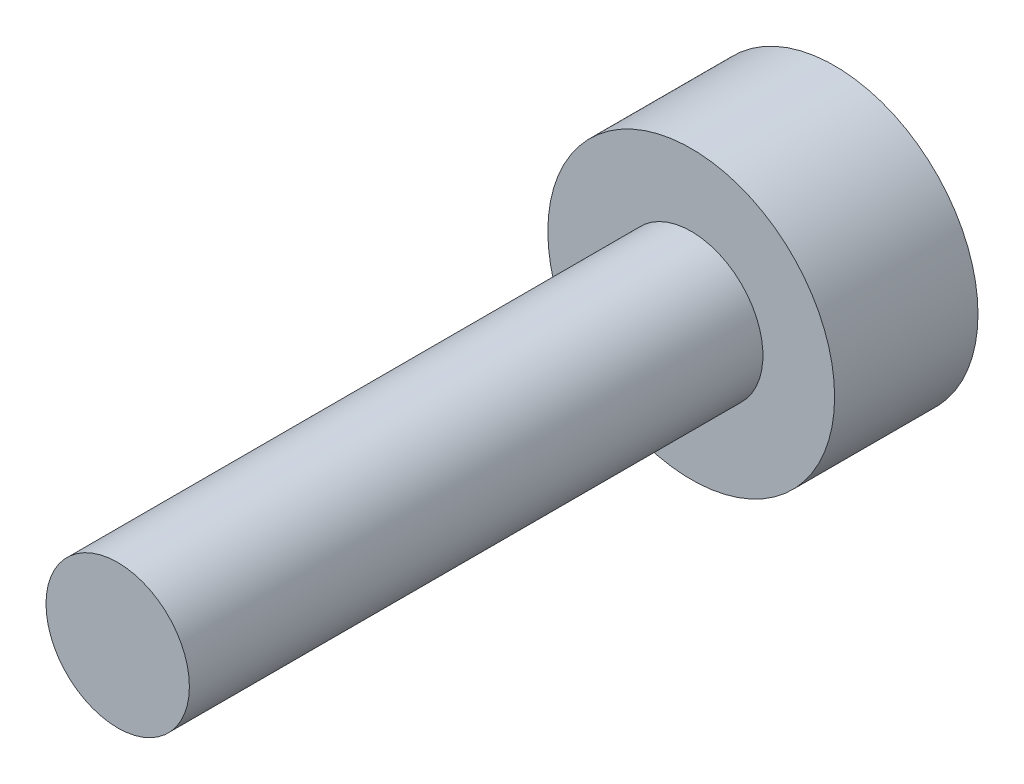
SolidWorks part; units mm, degrees
ref_plane "前视基准面" through (0, 0, 0) normal (0, 0, 1) x (1, 0, 0)
ref_plane "上视基准面" through (0, 0, 0) normal (0, 1, 0) x (1, 0, 0)
ref_plane "右视基准面" through (0, 0, 0) normal (1, 0, 0) x (0, 0, -1)
sketch "草图1" plane through (0, 0, 0) normal (0, 0, 1) x (1, 0, 0)
  circle A0 centre (0, 0) radius 1.5
extrude "凸台-拉伸1" add sketch "草图1" along normal blind 12
sketch "草图3" plane through (0, 0, 0) normal (0, 0, -1) x (-1, 0, 0)
  circle A0 centre (0, 0) radius 3
extrude "凸台-拉伸2" add sketch "草图3" along normal blind 3
